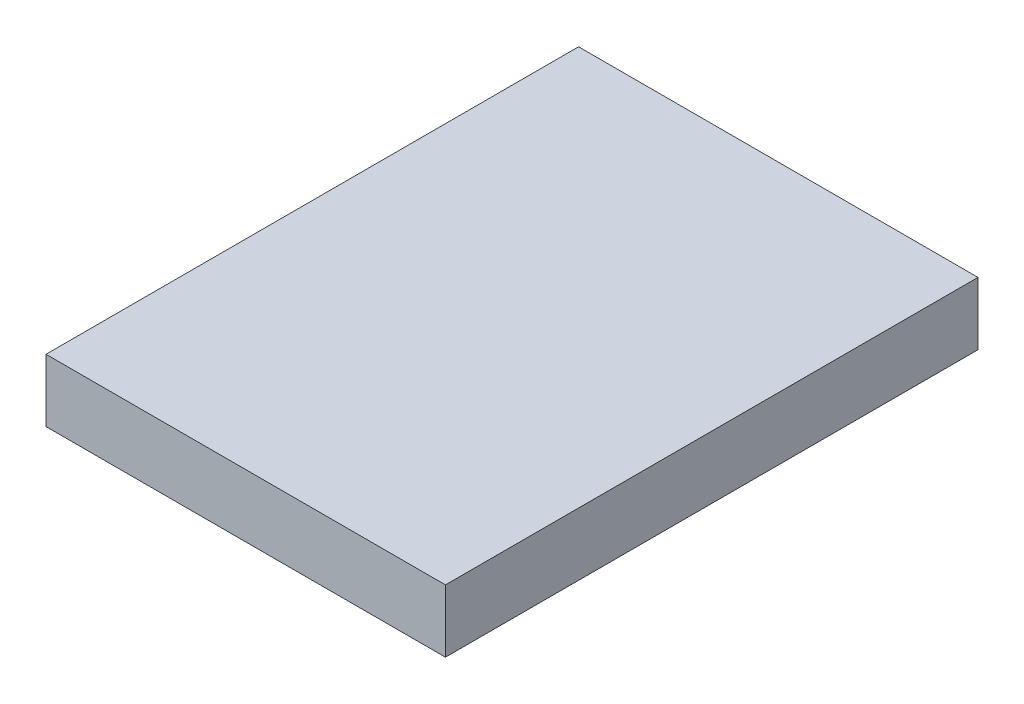
SolidWorks part; units mm, degrees
ref_plane "Front Plane" through (0, 0, 0) normal (0, 0, 1) x (1, 0, 0)
ref_plane "Top Plane" through (0, 0, 0) normal (0, 1, 0) x (1, 0, 0)
ref_plane "Right Plane" through (0, 0, 0) normal (1, 0, 0) x (0, 0, -1)
sketch "Sketch1" plane through (0, 0, 0) normal (0, 0, 1) x (1, 0, 0)
  line L1 (-38.25, -6) -> (38.25, -6)
  line L2 (-38.25, -6) -> (-38.25, 6)
  line L3 (-38.25, 6) -> (38.25, 6)
  line L4 (38.25, -6) -> (38.25, 6)
  line L5 (-38.25, -6) -> (38.25, 6) construction
  line L6 (-38.25, 6) -> (38.25, -6) construction
  point P0 (0, 0)
  dimension "D1" = 76.5
  dimension "D2" = 12
extrude "Boss-Extrude1" add sketch "Sketch1" along normal blind 102
